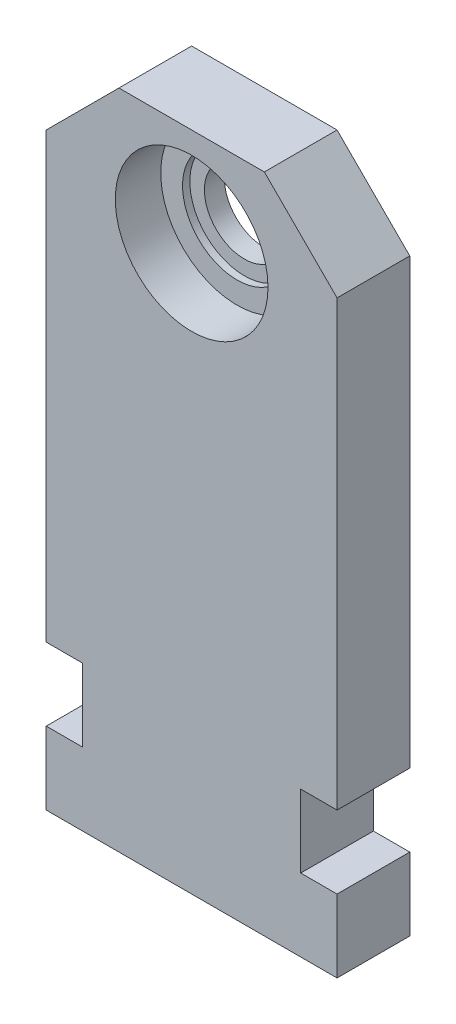
SolidWorks part; units mm, degrees
ref_plane "Plan de face" through (0, 0, 0) normal (0, 0, 1) x (1, 0, 0)
ref_plane "Plan de dessus" through (0, 0, 0) normal (0, 1, 0) x (1, 0, 0)
ref_plane "Plan de droite" through (0, 0, 0) normal (1, 0, 0) x (0, 0, -1)
sketch "Esquisse1" plane through (0, 0, 0) normal (0, 0, 1) x (1, 0, 0)
  line L1 (0, 0) -> (80, 0)
  line L2 (0, 0) -> (0, 182)
  line L3 (0, 182) -> (80, 182)
  line L4 (80, 0) -> (80, 182)
  dimension "D1" = 182
  dimension "D2" = 80
extrude "Boss.-Extru.1" add sketch "Esquisse1" along normal blind 20
sketch "Esquisse2" plane through (0, 0, 20) normal (0, 0, 1) x (1, 0, 0)
  line L0 (40, 0) -> (40, 155) construction
  line L1 (0, 0) -> (80, 0) construction
  circle A0 centre (40, 155) radius 11
  dimension "D1" = 22
  dimension "D2" = 155
extrude "Enlèv. mat.-Extru.1" cut sketch "Esquisse2" against normal through all both and the other way through all
chamfer "Chanfrein1" distance 20 angle 45 2 edges at (80, 182, 10) (0, 182, 10)
sketch "Esquisse3" plane through (0, 0, 20) normal (0, 0, 1) x (1, 0, 0)
  circle A0 centre (40, 155) radius 21
  dimension "D1" = 42
extrude "Enlèv. mat.-Extru.2" cut sketch "Esquisse3" against normal blind 12.5
sketch "Esquisse4" plane through (0, 0, 7.5) normal (0, 0, 1) x (1, 0, 0)
  circle A0 centre (40, 155) radius 15
  dimension "D1" = 30
extrude "Enlèv. mat.-Extru.3" cut sketch "Esquisse4" against normal blind 2
sketch "Esquisse5" plane through (0, 0, 20) normal (0, 0, 1) x (1, 0, 0)
  line L0 (40, 0) -> (40, 122.994) construction
  line L1 (0, 0) -> (80, 0) construction
  line L2 (80, 0) -> (80, 162) construction
  line L3 (80, 20) -> (70, 20)
  line L4 (80, 20) -> (80, 40)
  line L5 (80, 40) -> (70, 40)
  line L6 (70, 20) -> (70, 40)
  line L7 (10, 20) -> (10, 40)
  line L8 (0, 40) -> (10, 40)
  line L9 (0, 20) -> (0, 40)
  line L10 (0, 20) -> (10, 20)
  dimension "D1" = 10
  dimension "D2" = 20
  dimension "D3" = 20
extrude "Enlèv. mat.-Extru.4" cut sketch "Esquisse5" against normal through all both and the other way through all
